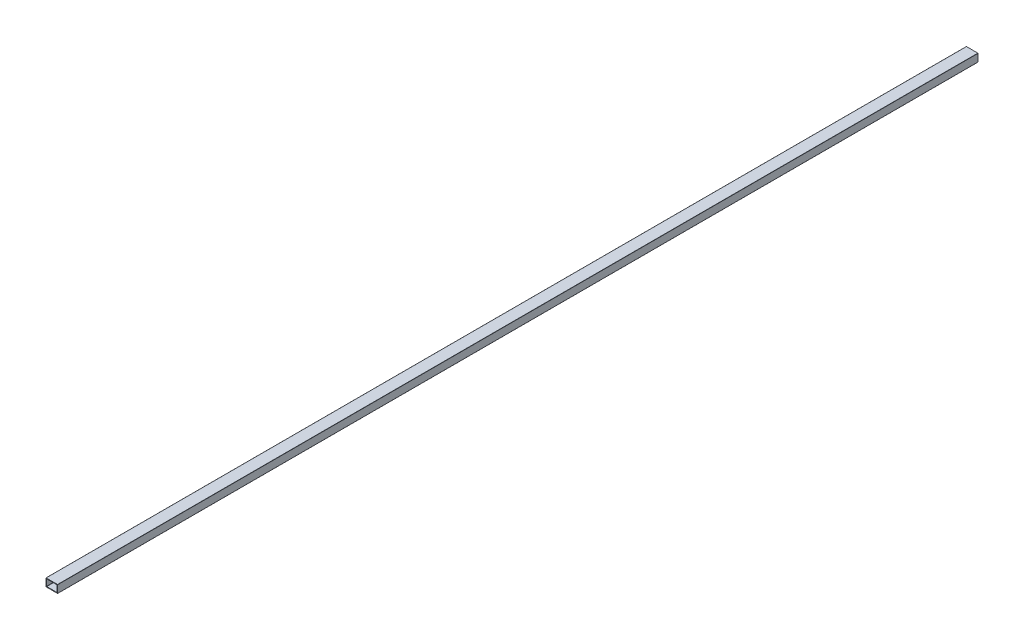
SolidWorks part; units mm, degrees
material "AISI 1035 Acero (SS)"
ref_plane "Alzado" through (0, 0, 0) normal (0, 0, 1) x (1, 0, 0)
ref_plane "Planta" through (0, 0, 0) normal (0, 1, 0) x (1, 0, 0)
ref_plane "Vista lateral" through (0, 0, 0) normal (1, 0, 0) x (0, 0, -1)
sketch "Croquis1" plane through (0, 0, 0) normal (0, 0, 1) x (1, 0, 0)
  line L0 (-34.3, -21.6) -> (-34.3, 21.6)
  line L1 (-38.1, -25.4) -> (38.1, -25.4)
  line L2 (-38.1, -25.4) -> (-38.1, 25.4)
  line L3 (-38.1, 25.4) -> (38.1, 25.4)
  line L4 (38.1, -25.4) -> (38.1, 25.4)
  line L5 (-38.1, -25.4) -> (38.1, 25.4) construction
  line L6 (-38.1, 25.4) -> (38.1, -25.4) construction
  line L7 (-34.3, 21.6) -> (34.3, 21.6)
  line L8 (34.3, -21.6) -> (34.3, 21.6)
  line L9 (-34.3, -21.6) -> (34.3, -21.6)
  point P0 (0, 0)
  dimension "D1" = 50.8
  dimension "D2" = 76.2
  dimension "D3" = 3.8
extrude "Saliente-Extruir1" add sketch "Croquis1" against normal blind 6000
fillet "Redondeo1" radius 1 8 edges at (-34.3, 21.6, -3000) (34.3, 21.6, -3000) (34.3, -21.6, -3000) (-38.1, -25.4, -3000) (-38.1, 25.4, -3000) (-34.3, -21.6, -3000) (38.1, -25.4, -3000) (38.1, 25.4, -3000)
